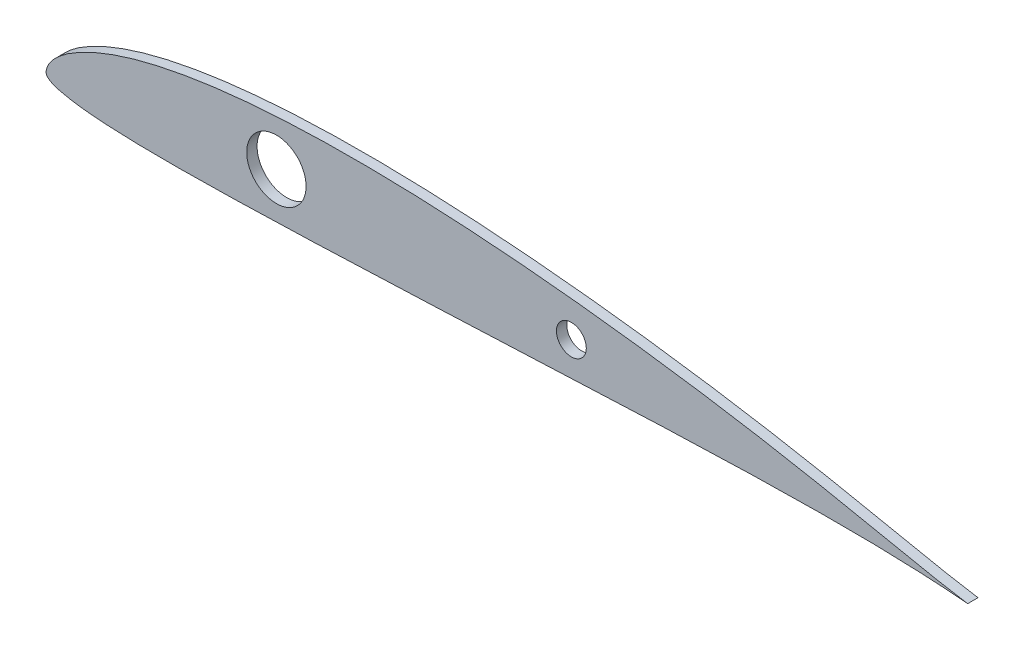
SolidWorks part; units mm, degrees
material "Фанера"
ref_plane "Front Plane" through (0, 0, 0) normal (0, 0, 1) x (1, 0, 0)
ref_plane "Top Plane" through (0, 0, 0) normal (0, 1, 0) x (1, 0, 0)
ref_plane "Right Plane" through (0, 0, 0) normal (1, 0, 0) x (0, 0, -1)
curve "Кривая3"
  spline degree 3 poles (0, 0, 0) (0.0189, -0.1915, 0) (0.0951, -0.9647, 0) (1.7062, -2.107, 0) (4.5001, -2.8518, 0) (8.6875, -3.6441, 0) (14.1357, -4.1591, 0) (20.8481, -4.5235, 0) (28.7529, -4.6885, 0) (37.7798, -4.689, 0) (47.8378, -4.538, 0) (58.8203, -4.2519, 0) (70.6068, -3.8686, 0) (83.0601, -3.409, 0) (96.0356, -2.8793, 0) (109.3872, -2.3064, 0) (122.966, -1.6949, 0) (136.6221, -1.0736, 0) (150.1991, -0.4709, 0) (163.5366, 0.0766, 0) (176.4711, 0.5668, 0) (188.8411, 0.9576, 0) (200.4839, 1.2281, 0) (211.2346, 1.3582, 0) (220.9267, 1.3477, 0) (229.3961, 1.1809, 0) (236.4968, 0.9175, 0) (242.1145, 0.6071, 0) (246.1753, 0.3331, 0) (248.6289, 0.1254, 0) (249.725, 0.0252, 0) (250, 0, 0) knots 0 0 0 0 0.00225 0.009086 0.020842 0.037635 0.059467 0.086252 0.117796 0.153827 0.193968 0.237839 0.284933 0.334701 0.386556 0.43991 0.494184 0.548768 0.60305 0.656369 0.708069 0.757519 0.804064 0.847048 0.885824 0.919723 0.948136 0.970615 0.986864 0.996705 1 1 1 1
curve "Кривая4"
  spline degree 3 poles (250, 0, 0) (249.7283, 0.0396, 0) (248.6529, 0.1962, 0) (246.2795, 0.5872, 0) (242.4284, 1.2884, 0) (237.2229, 2.3094, 0) (230.7938, 3.6234, 0) (223.2699, 5.1719, 0) (214.7745, 6.8952, 0) (205.4215, 8.7148, 0) (195.3158, 10.558, 0) (184.5597, 12.3678, 0) (173.2575, 14.0983, 0) (161.5237, 15.7183, 0) (149.4778, 17.1911, 0) (137.2447, 18.4899, 0) (124.9484, 19.577, 0) (112.7133, 20.4235, 0) (100.6601, 21.0051, 0) (88.9026, 21.2979, 0) (77.55, 21.2892, 0) (66.7052, 20.9647, 0) (56.4629, 20.3206, 0) (46.9046, 19.356, 0) (38.1027, 18.0641, 0) (30.1163, 16.5025, 0) (22.9979, 14.6774, 0) (16.7956, 12.6105, 0) (11.5276, 10.3909, 0) (7.2273, 8.0852, 0) (3.9, 5.7711, 0) (1.6011, 3.5039, 0) (0.3352, 1.5562, 0) (0.0815, 0.3784, 0) (0, 0, 0) knots 0 0 0 0 0.0032 0.012665 0.028032 0.04882 0.074488 0.104508 0.138345 0.175514 0.215555 0.258062 0.30263 0.348808 0.396106 0.444059 0.492175 0.539965 0.586986 0.632802 0.677022 0.71928 0.75923 0.796603 0.831211 0.862874 0.891404 0.916794 0.939003 0.957939 0.973592 0.986016 0.995508 1 1 1 1
sketch "Эскиз1" plane through (0, 0, 0) normal (0, 0, 1) x (1, 0, 0)
  line L0 (0, 0) -> (250.8655, 0) construction
  line L1 (250, 0) -> (250, 46.2865) construction
  line L2 (0, 0) -> (0, 51.906) construction
  line L3 (62.5, 67.5411) -> (62.5, -43.8522) construction
  line L4 (142.5, 62.6267) -> (142.5, -53.8612) construction
  circle A0 centre (62.5, 8.2779) radius 8.05
  circle A1 centre (142.5, 8.2779) radius 4.05
  spline S0 degree 3 poles (-2754.7551, -1186.2364) (64.7022, 44.8443) (-7.1294, 4.1578) (1.7062, -2.107) (4.5001, -2.8518) (8.6875, -3.6441) (14.1357, -4.1591) (20.8481, -4.5235) (28.7529, -4.6885) (37.7798, -4.689) (47.8378, -4.538) (58.8203, -4.2519) (70.6068, -3.8686) (83.0601, -3.409) (96.0356, -2.8793) (109.3872, -2.3064) (122.966, -1.6949) (136.6221, -1.0736) (150.1991, -0.4709) (163.5366, 0.0766) (176.4711, 0.5668) (188.8411, 0.9576) (200.4839, 1.2281) (211.2346, 1.3582) (220.9267, 1.3477) (229.3961, 1.1809) (236.4968, 0.9175) (242.1145, 0.6071) (246.1753, 0.3331) (299.5829, -4.1866) (350.0781, -25.3884) (678.8337, 2966.8017) knots -0.093463 -0.093463 -0.093463 -0.093463 0.00225 0.009086 0.020842 0.037635 0.059467 0.086252 0.117796 0.153827 0.193968 0.237839 0.284933 0.334701 0.386556 0.43991 0.494184 0.548768 0.60305 0.656369 0.708069 0.757519 0.804064 0.847048 0.885824 0.919723 0.948136 0.970615 0.986864 0.996705 1.610235 1.610235 1.610235 1.610235 only from (0, 0) to (250, 0) construction
  spline S1 degree 3 poles (-89.4628, -2979.2708) (325.0091, 11.9689) (284.5016, -5.7094) (246.2795, 0.5872) (242.4284, 1.2884) (237.2229, 2.3094) (230.7938, 3.6234) (223.2699, 5.1719) (214.7745, 6.8952) (205.4215, 8.7148) (195.3158, 10.558) (184.5597, 12.3678) (173.2575, 14.0983) (161.5237, 15.7183) (149.4778, 17.1911) (137.2447, 18.4899) (124.9484, 19.577) (112.7133, 20.4235) (100.6601, 21.0051) (88.9026, 21.2979) (77.55, 21.2892) (66.7052, 20.9647) (56.4629, 20.3206) (46.9046, 19.356) (38.1027, 18.0641) (30.1163, 16.5025) (22.9979, 14.6774) (16.7956, 12.6105) (11.5276, 10.3909) (7.2273, 8.0852) (3.9, 5.7711) (1.6011, 3.5039) (-8.3638, -11.8281) (63.6578, -54.8701) (-2844.3181, 951.0549) knots -0.423398 -0.423398 -0.423398 -0.423398 0.0032 0.012665 0.028032 0.04882 0.074488 0.104508 0.138345 0.175514 0.215555 0.258062 0.30263 0.348808 0.396106 0.444059 0.492175 0.539965 0.586986 0.632802 0.677022 0.71928 0.75923 0.796603 0.831211 0.862874 0.891404 0.916794 0.939003 0.957939 0.973592 0.986016 0.995508 1.181475 1.181475 1.181475 1.181475 only from (250, 0) to (0, 0) construction
  spline S2 degree 3 poles (0, 0) (0.0189, -0.1915) (0.0951, -0.9647) (1.7062, -2.107) (4.5001, -2.8518) (8.6875, -3.6441) (14.1357, -4.1591) (20.8481, -4.5235) (28.7529, -4.6885) (37.7798, -4.689) (47.8378, -4.538) (58.8203, -4.2519) (70.6068, -3.8686) (83.0601, -3.409) (96.0356, -2.8793) (109.3872, -2.3064) (122.966, -1.6949) (136.6221, -1.0736) (150.1991, -0.4709) (163.5366, 0.0766) (176.4711, 0.5668) (188.8411, 0.9576) (200.4839, 1.2281) (211.2346, 1.3582) (220.9267, 1.3477) (229.3961, 1.1809) (236.4968, 0.9175) (242.1145, 0.6071) (246.1753, 0.3331) (248.6289, 0.1254) (249.725, 0.0252) (250, 0) knots 0 0 0 0 0.00225 0.009086 0.020842 0.037635 0.059467 0.086252 0.117796 0.153827 0.193968 0.237839 0.284933 0.334701 0.386556 0.43991 0.494184 0.548768 0.60305 0.656369 0.708069 0.757519 0.804064 0.847048 0.885824 0.919723 0.948136 0.970615 0.986864 0.996705 1 1 1 1
  spline S3 degree 3 poles (250, 0) (249.7283, 0.0396) (248.6529, 0.1962) (246.2795, 0.5872) (242.4284, 1.2884) (237.2229, 2.3094) (230.7938, 3.6234) (223.2699, 5.1719) (214.7745, 6.8952) (205.4215, 8.7148) (195.3158, 10.558) (184.5597, 12.3678) (173.2575, 14.0983) (161.5237, 15.7183) (149.4778, 17.1911) (137.2447, 18.4899) (124.9484, 19.577) (112.7133, 20.4235) (100.6601, 21.0051) (88.9026, 21.2979) (77.55, 21.2892) (66.7052, 20.9647) (56.4629, 20.3206) (46.9046, 19.356) (38.1027, 18.0641) (30.1163, 16.5025) (22.9979, 14.6774) (16.7956, 12.6105) (11.5276, 10.3909) (7.2273, 8.0852) (3.9, 5.7711) (1.6011, 3.5039) (0.3352, 1.5562) (0.0815, 0.3784) (0, 0) knots 0 0 0 0 0.0032 0.012665 0.028032 0.04882 0.074488 0.104508 0.138345 0.175514 0.215555 0.258062 0.30263 0.348808 0.396106 0.444059 0.492175 0.539965 0.586986 0.632802 0.677022 0.71928 0.75923 0.796603 0.831211 0.862874 0.891404 0.916794 0.939003 0.957939 0.973592 0.986016 0.995508 1 1 1 1
  point P13 (62.5, 20.6838)
  point P14 (62.5, -4.128)
  point P15 (0, 0)
  dimension "D4" = 16.1
  dimension "D5" = 8.1
  dimension "D1" = 250
  dimension "D2" = 62.5
  dimension "D3" = 80
  dimension "D6" = 24.8118
  dimension "D7" = 12.4059
extrude "Бобышка-Вытянуть1" add sketch "Эскиз1" along normal mid plane 2.8
equation "\"D2@Эскиз1\"=\"D1@Эскиз1\"/4"
equation "\"D7@Эскиз1\"=\"D6@Эскиз1\"/2"
